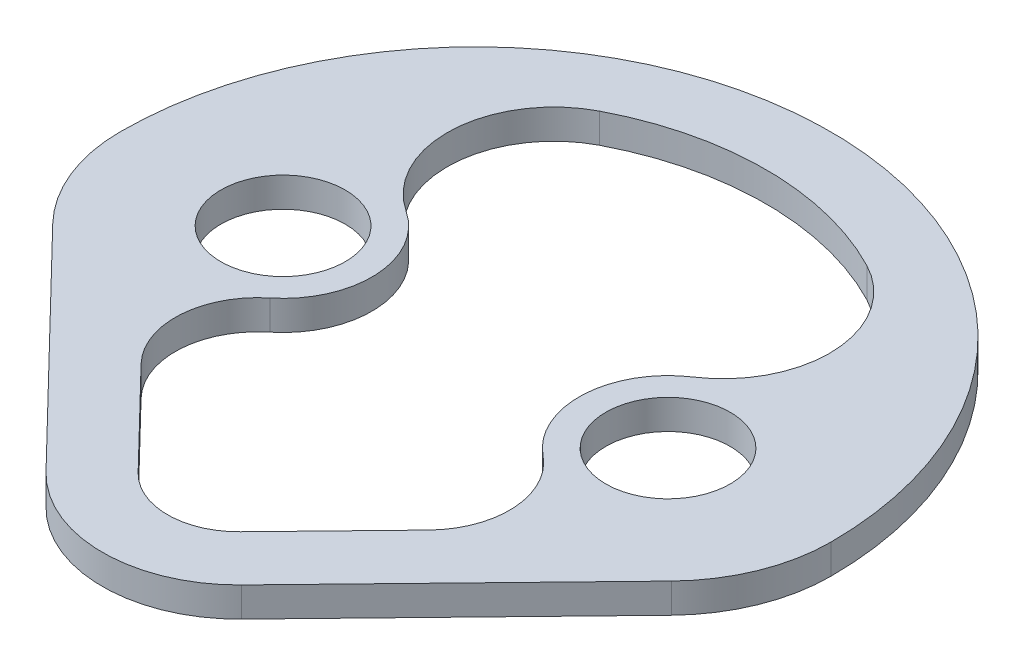
SolidWorks part; units mm, degrees
ref_plane "Front Plane" through (0, 0, 0) normal (0, 0, 1) x (1, 0, 0)
ref_plane "Top Plane" through (0, 0, 0) normal (0, 1, 0) x (1, 0, 0)
ref_plane "Right Plane" through (0, 0, 0) normal (1, 0, 0) x (0, 0, -1)
sketch "Sketch1" plane through (0, 0, 0) normal (0, 1, 0) x (1, 0, 0)
  line L0 (0, 192.8503) -> (0, -129.6586) construction
  line L1 (16.5161, -16.0068) -> (52.2475, 20.8614)
  line L2 (8.6171, -8.3514) -> (24.2889, 7.819)
  line L3 (8.6171, -8.3514) -> (44.3485, 28.5168) construction
  line L4 (-8.6171, -8.3514) -> (-24.2889, 7.819)
  line L5 (-16.5161, -16.0068) -> (-52.2475, 20.8614)
  circle A0 centre (32.5, 40) radius 10.5
  arc A1 (23.0558, 28.3464) -> (24.2185, 52.5067) centre (32.5, 40) cw
  arc A2 (60, 40) -> (0, 100) centre (0, 40) ccw
  arc A3 (0, -23) -> (16.5161, -16.0068) centre (0, 0) ccw
  arc A4 (22.5728, 83.491) -> (-22.5728, 83.491) centre (0, 40) ccw
  arc A5 (49, 40) -> (0, 89) centre (0, 40) ccw construction
  arc A6 (0, -12) -> (8.6171, -8.3514) centre (0, 0) ccw
  arc A7 (22.5728, 83.491) -> (24.2185, 52.5067) centre (14.2808, 67.5147) cw
  arc A8 (23.0558, 28.3464) -> (24.2889, 7.819) centre (14.2808, 17.5185) cw
  arc A9 (60, 40) -> (52.2475, 20.8614) centre (32.5, 40) cw
  circle A10 centre (-32.5, 40) radius 10.5
  arc A11 (0, -23) -> (-16.5161, -16.0068) centre (0, 0) cw
  arc A12 (0, -12) -> (-8.6171, -8.3514) centre (0, 0) cw
  arc A13 (-23.0558, 28.3464) -> (-24.2889, 7.819) centre (-14.2808, 17.5185) ccw
  arc A14 (-60, 40) -> (-52.2475, 20.8614) centre (-32.5, 40) ccw
  arc A15 (-23.0558, 28.3464) -> (-24.2185, 52.5067) centre (-32.5, 40) ccw
  arc A16 (-22.5728, 83.491) -> (-24.2185, 52.5067) centre (-14.2808, 67.5147) ccw
  arc A17 (-60, 40) -> (0, 100) centre (0, 40) cw
  point P16 (14.2808, 17.4867)
  point P22 (14.2808, 17.4877)
  point P25 (14.2808, 17.4838)
  point P26 (0, 0)
  point P27 (11.57, 17.4013)
  point P28 (0, 0)
  point P29 (0, 0)
  dimension "D1" = 21
  dimension "D4" = 60
  dimension "D5" = 23
  dimension "D7" = 18
  dimension "D8" = 15
  dimension "D2" = 40
  dimension "D3" = 32.5
  dimension "D6" = 11
  dimension "D9" = 11
extrude "Boss-Extrude2" add sketch "Sketch1" along normal blind 5
